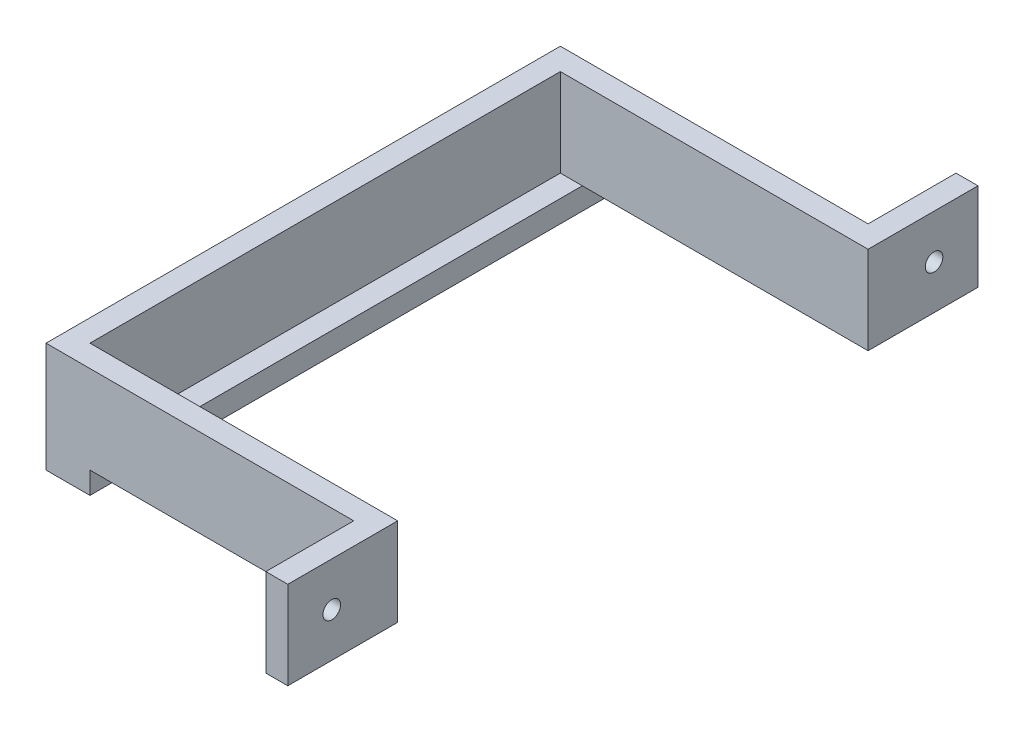
SolidWorks part; units mm, degrees
ref_plane "Front Plane" through (0, 0, 0) normal (0, 0, 1) x (1, 0, 0)
ref_plane "Top Plane" through (0, 0, 0) normal (0, 1, 0) x (1, 0, 0)
ref_plane "Right Plane" through (0, 0, 0) normal (1, 0, 0) x (0, 0, -1)
sketch "Sketch1" plane through (0, 0, 0) normal (1, 0, 0) x (0, 0, -1)
  line L1 (-58.5, 10) -> (58.5, 10)
  line L2 (-58.5, 10) -> (-58.5, -10)
  line L3 (-58.5, -10) -> (58.5, -10)
  line L4 (58.5, 10) -> (58.5, -10)
  line L5 (-58.5, 10) -> (58.5, -10) construction
  line L6 (-58.5, -10) -> (58.5, 10) construction
  point P0 (0, 0)
extrude "Boss-Extrude1" add sketch "Sketch1" along normal blind 5
sketch "Sketch2" plane through (5, 0, 0) normal (1, 0, 0) x (0, 0, -1)
  line L0 (-58.5, -10) -> (58.5, -10) construction
  line L1 (-58.5, 10) -> (-53.5, 10)
  line L2 (-58.5, 10) -> (-58.5, -10)
  line L3 (-58.5, -10) -> (-53.5, -10)
  line L4 (-53.5, 10) -> (-53.5, -10)
  line L6 (58.5, 10) -> (53.5, 10)
  line L7 (58.5, 10) -> (58.5, -10)
  line L8 (58.5, -10) -> (53.5, -10)
  line L9 (53.5, 10) -> (53.5, -10)
extrude "Boss-Extrude2" add sketch "Sketch2" along normal blind 70
sketch "Sketch3" plane through (0, -10, 0) normal (0, -1, 0) x (1, 0, 0)
  line L0 (75, -58.5) -> (0, -58.5) construction
  line L1 (0, 58.5) -> (10, 58.5)
  line L2 (0, 58.5) -> (0, -58.5)
  line L3 (0, -58.5) -> (10, -58.5)
  line L4 (10, 58.5) -> (10, -58.5)
extrude "Boss-Extrude3" add sketch "Sketch3" along normal blind 5
sketch "Sketch4" plane through (0, 0, 58.5) normal (0, 0, 1) x (1, 0, 0)
  line L0 (75, -10) -> (10, -10) construction
  line L1 (75, 10) -> (70, 10)
  line L2 (75, 10) -> (75, -10)
  line L3 (75, -10) -> (70, -10)
  line L4 (70, 10) -> (70, -10)
extrude "Boss-Extrude4" add sketch "Sketch4" along normal blind 20
sketch "Sketch5" plane through (0, 0, -58.5) normal (0, 0, -1) x (-1, 0, 0)
  line L0 (-75, -10) -> (-10, -10) construction
  line L1 (-75, 10) -> (-70, 10)
  line L2 (-75, 10) -> (-75, -10)
  line L3 (-75, -10) -> (-70, -10)
  line L4 (-70, 10) -> (-70, -10)
extrude "Boss-Extrude5" add sketch "Sketch5" along normal blind 20
sketch "Sketch6" plane through (70, 0, 0) normal (-1, 0, 0) x (0, 0, 1)
  circle A0 centre (-68.5, 0) radius 2
  circle A1 centre (68.5, 0) radius 2
  point P4 (-68.5, -10)
  point P5 (-68.5, 0)
  point P10 (62.0077, -10)
  point P11 (68.5, 0)
extrude "Cut-Extrude1" cut sketch "Sketch6" against normal blind 5
